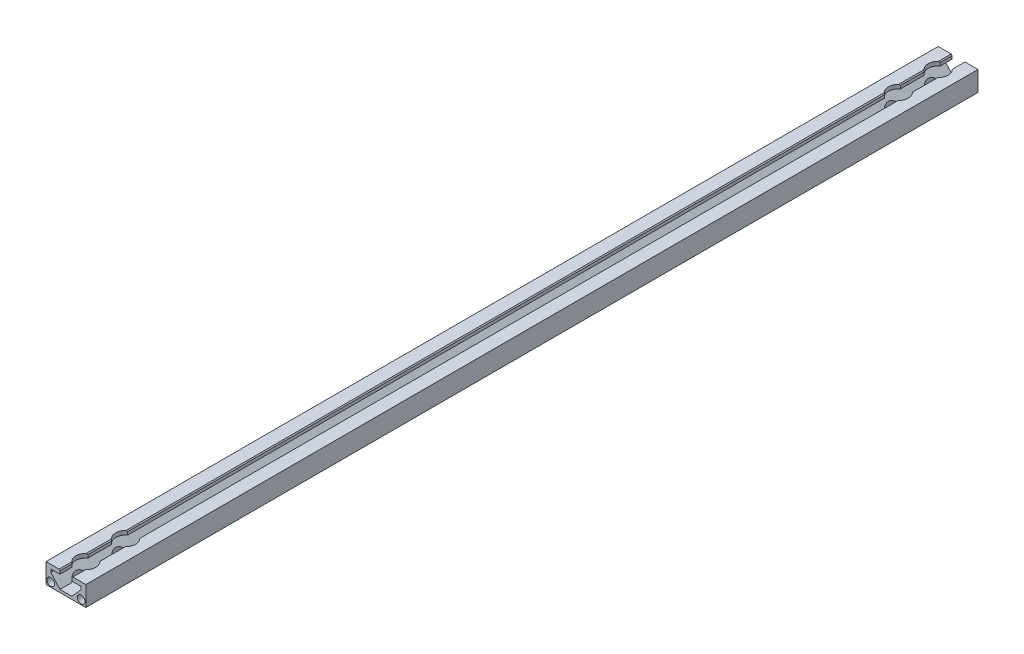
SolidWorks part; units mm, degrees
ref_plane "Front Plane" through (0, 0, 0) normal (0, 0, 1) x (1, 0, 0)
ref_plane "Top Plane" through (0, 0, 0) normal (0, 1, 0) x (1, 0, 0)
ref_plane "Right Plane" through (0, 0, 0) normal (1, 0, 0) x (0, 0, -1)
sketch "Sketch1" plane through (0, 0, 0) normal (0, 0, 1) x (1, 0, 0)
  line L0 (0, 0) -> (0, -1.383)
  line L1 (0, -1.383) -> (10, -1.383)
  line L2 (10, -1.383) -> (10, 8.617)
  line L3 (10, 8.617) -> (3.4482, 8.617)
  line L4 (3.4482, 8.617) -> (3, 8.117)
  line L5 (3, 8.117) -> (3, 6.617)
  line L6 (3, 6.617) -> (7.587, 6.617)
  line L7 (7.587, 6.617) -> (7.587, 5.117)
  line L8 (7.587, 5.117) -> (3, 0)
  line L9 (3, 0) -> (0, 0)
  dimension "D1" = 10
  dimension "D2" = 10
  dimension "D3" = 3
  dimension "D4" = 1.5
  dimension "D5" = 3
  dimension "D6" = 2
  dimension "D7" = 1.5
extrude "Boss-Extrude1" add sketch "Sketch1" along normal mid plane 448
mirror "Mirror1" about plane through (0, 0, 0) normal (1, 0, 0) of "Boss-Extrude1"
sketch "Sketch2" plane through (0, 0, 224) normal (0, 0, 1) x (1, 0, 0)
  line L0 (10, -1.383) -> (5.6551, 2.9619) construction
  line L1 (7.587, 5.117) -> (3, 0) construction
  circle A0 centre (7.6467, 0.9703) radius 1.9
  dimension "D1" = 3.8
extrude "Cut-Extrude1" cut sketch "Sketch2" against normal through all
mirror "Mirror2" about plane through (0, 0, 0) normal (1, 0, 0) of "Cut-Extrude1"
sketch "Sketch3" plane through (0, -1.383, 0) normal (0, -1, 0) x (1, 0, 0)
  line L0 (0, 140) -> (0, -140) construction
  line L1 (10, 224) -> (10, -224) construction
  circle A0 centre (0, 140) radius 2.5
  circle A1 centre (0, -140) radius 2.5
  point P6 (10, 0)
  point P7 (0, 0)
  dimension "D2" = 5
  dimension "D3" = 5
  dimension "D1" = 280
extrude "Cut-Extrude2" cut sketch "Sketch3" against normal through all
hole_wizard "M4 Clearance Hole1" positions "Sketch4" profile "Sketch5" hole size "M4" standard "ANSI Metric" end condition through all
sketch "Sketch4" plane through (0, -1.383, 0) normal (0, -1, 0) x (-1, 0, 0)
  line L0 (10, -224) -> (-10, -224) construction
  line L1 (0, -142.5) -> (0, -194) construction
  line L2 (0, -194) -> (0, -214) construction
  circle A0 centre (0, -140) radius 2.5 construction
  point P0 (0, -214)
  point P2 (0, -194)
  dimension "D1" = 20
  dimension "D2" = 10
sketch "Sketch5" plane through (0, -1.383, 214) normal (1, 0, 0) x (0, 0, -1)
  line L0 (0, 0) -> (0, 10)
  line L1 (0, 10) -> (2.4, 10)
  line L2 (2.4, 10) -> (2.4, 0)
  line L5 (2.4, 0) -> (0, 0)
  line L11 (0, -6.35) -> (0, 107.95) construction
  dimension "Thru Hole Dia." = 4.8
  dimension "Thru Hole Depth" = 10
mirror "Mirror3" about plane through (0, 0, 0) normal (0, 0, 1) of "M4 Clearance Hole1"
sketch "Sketch6" plane through (0, 8.617, 0) normal (0, 1, 0) x (1, 0, 0)
  circle A0 centre (0, -214) radius 5
  circle A1 centre (0, -194) radius 5
  dimension "D1" = 10
  dimension "D2" = 10
extrude "Cut-Extrude3" cut sketch "Sketch6" against normal up to surface (8.617 mm away) up to face at (2.4, 0, -214)
mirror "Mirror4" about plane through (0, 0, 0) normal (0, 0, 1) of "Cut-Extrude3"
